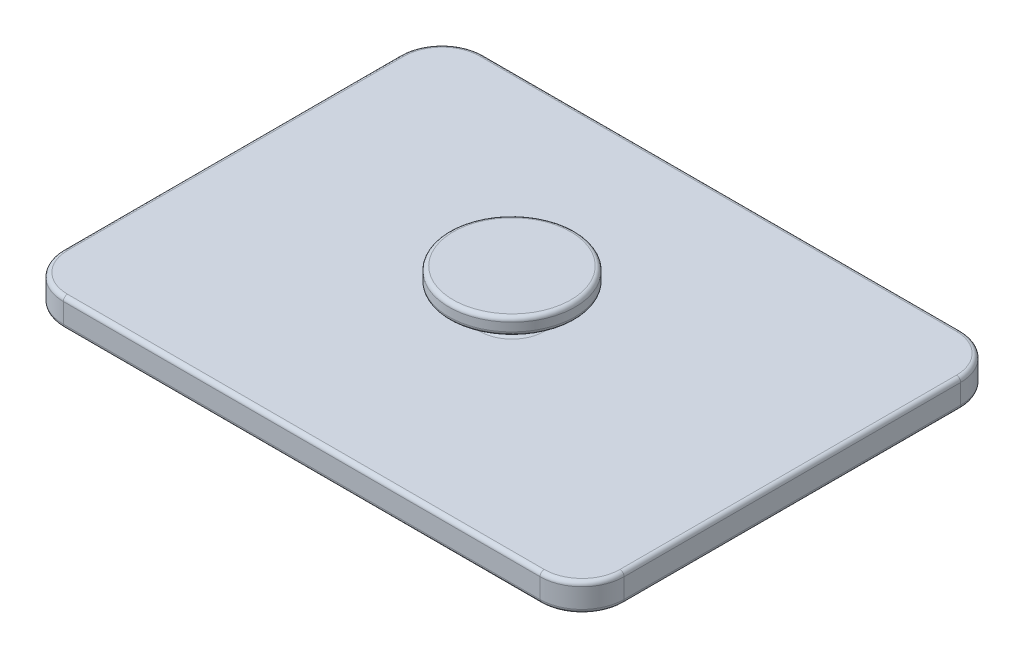
SolidWorks part; units mm, degrees
ref_plane "Front Plane" through (0, 0, 0) normal (0, 0, 1) x (1, 0, 0)
ref_plane "Top Plane" through (0, 0, 0) normal (0, 1, 0) x (1, 0, 0)
ref_plane "Right Plane" through (0, 0, 0) normal (1, 0, 0) x (0, 0, -1)
sketch "Sketch1" plane through (0, -20, 0) normal (0, -1, 0) x (1, 0, 0)
  circle A0 centre (0, 0) radius 4.5
  dimension "D1" = 9
extrude "Boss-Extrude1" add sketch "Sketch1" along normal blind 1.2
sketch "Sketch2" plane through (0, -21.2, 0) normal (0, -1, 0) x (1, 0, 0)
  circle A0 centre (0, 0) radius 2
  dimension "D1" = 4
extrude "Boss-Extrude2" add sketch "Sketch2" along normal blind 1.7
sketch "Sketch4" plane through (0, -22.9, 0) normal (0, -1, 0) x (1, 0, 0)
  line L1 (20, -15) -> (-20, -15)
  line L2 (20, -15) -> (20, 15)
  line L3 (20, 15) -> (-20, 15)
  line L4 (-20, -15) -> (-20, 15)
  line L5 (20, -15) -> (-20, 15) construction
  line L6 (20, 15) -> (-20, -15) construction
  point P0 (0, 0)
  dimension "D1" = 30
  dimension "D2" = 40
extrude "Boss-Extrude3" add sketch "Sketch4" along normal blind 2
fillet "Fillet1" radius 3 4 edges at (20, -23.9, -15) (20, -23.9, 15) (-20, -23.9, 15) (-20, -23.9, -15)
fillet "Fillet2" radius 0.3 8 edges at (-19.1213, -24.9, -14.1213) (-20, -24.9, 0) (-19.1213, -24.9, 14.1213) (0, -24.9, 15) (19.1213, -24.9, 14.1213) (20, -24.9, 0) (19.1213, -24.9, -14.1213) (0, -24.9, -15)
fillet "Fillet3" radius 0.3 8 edges at (-19.1213, -22.9, -14.1213) (-20, -22.9, 0) (-19.1213, -22.9, 14.1213) (0, -22.9, 15) (19.1213, -22.9, 14.1213) (20, -22.9, 0) (19.1213, -22.9, -14.1213) (0, -22.9, -15)
fillet "Fillet4" radius 0.3 1 edges at (0, -21.2, -4.5)
fillet "Fillet5" radius 0.3 1 edges at (0, -20, -4.5)
fillet "Fillet6" radius 0.3 1 edges at (0, -22.9, -2)
fillet "Fillet7" radius 0.3 1 edges at (0, -21.2, -2)
